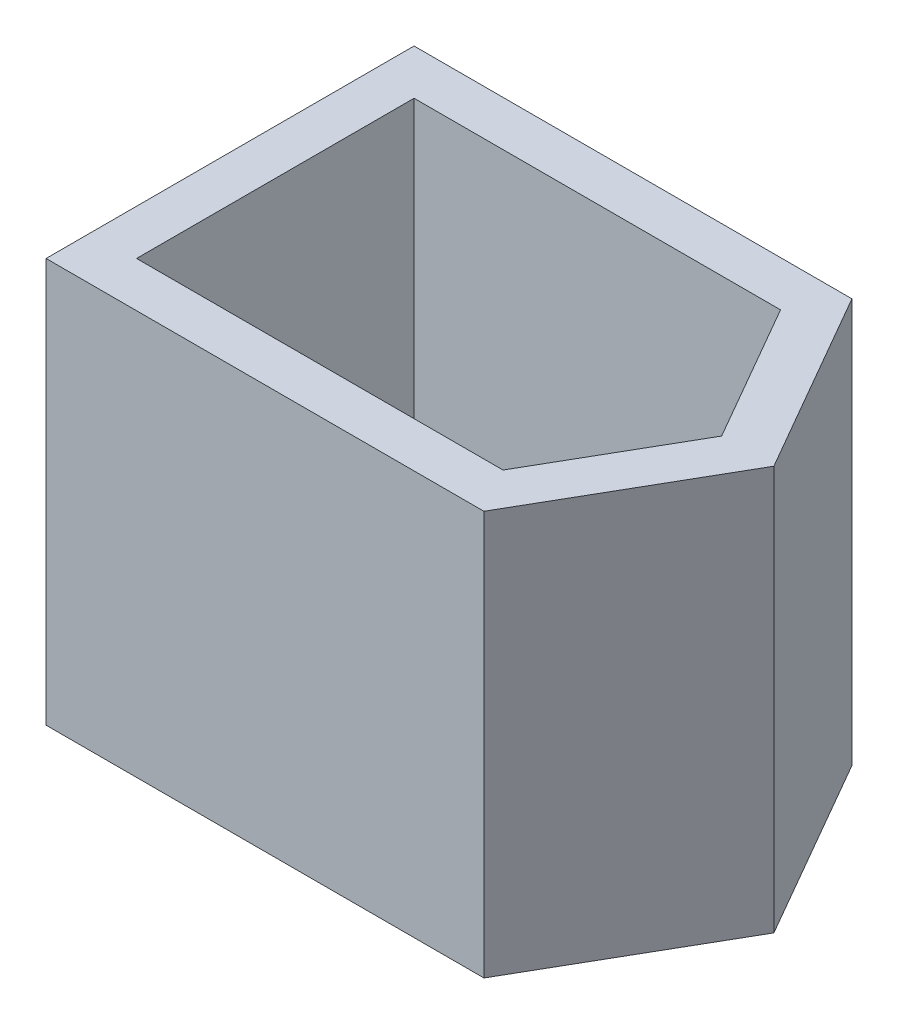
SolidWorks part; units mm, degrees
ref_plane "Front Plane" through (0, 0, 0) normal (0, 0, 1) x (1, 0, 0)
ref_plane "Top Plane" through (0, 0, 0) normal (0, 1, 0) x (1, 0, 0)
ref_plane "Right Plane" through (0, 0, 0) normal (1, 0, 0) x (0, 0, -1)
sketch "tangent" plane through (0, 0, 0) normal (0, 1, 0) x (1, 0, 0)
  line L0 (56.8, 0) -> (68.6, 20.5)
  line L1 (0, 0) -> (56.8, 0)
  line L2 (0, 0) -> (0, 41)
  line L3 (0, 41) -> (56.8, 41)
  line L5 (68.6, 20.5) -> (56.8, 41)
  line L6 (68.6, 20.5) -> (56.8, 20.5) construction
  line L7 (56.8, 41) -> (56.8, 0) construction
  point P9 (56.8, 20.5)
  dimension "D1" = 56.8
  dimension "D2" = 41
  dimension "D3" = 11.8
sketch "Sketch2" plane through (0, 0, 0) normal (0, 1, 0) x (1, 0, 0)
  line L5 (62.5822, 51) -> (-10, 51)
  line L6 (-10, 51) -> (-10, -10)
  line L7 (-10, -10) -> (62.5822, -10)
  line L8 (62.5822, -10) -> (80.1383, 20.5)
  line L9 (80.1383, 20.5) -> (62.5822, 51)
  line L10 (-2.5, 43.5) -> (-2.5, -2.5)
  line L11 (-2.5, -2.5) -> (58.2456, -2.5)
  line L12 (58.2456, -2.5) -> (71.4846, 20.5)
  line L13 (71.4846, 20.5) -> (58.2456, 43.5)
  line L14 (58.2456, 43.5) -> (-2.5, 43.5)
  line L15 (-2.5, 43.5) -> (-2.5, -2.5)
  line L16 (-2.5, -2.5) -> (58.2456, -2.5)
  line L17 (58.2456, -2.5) -> (71.4846, 20.5)
  line L18 (71.4846, 20.5) -> (58.2456, 43.5)
  line L19 (58.2456, 43.5) -> (-2.5, 43.5)
  dimension "D1" = 2.5
  dimension "D2" = 7.5
extrude "Boss-Extrude1" add sketch "Sketch2" along normal blind 67
